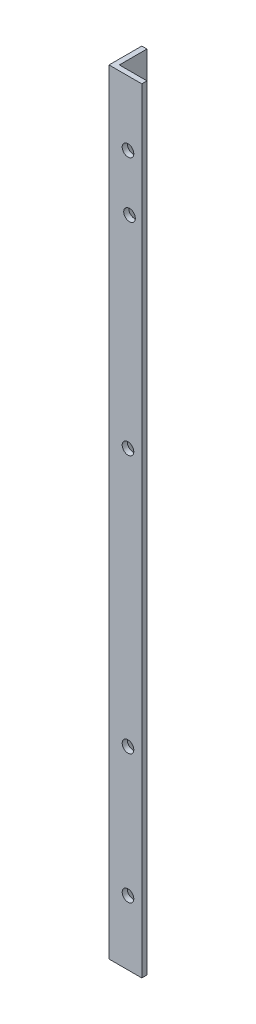
SolidWorks part; units mm, degrees
material "Alumina"
ref_plane "Front Plane" through (0, 0, 0) normal (0, 0, 1) x (1, 0, 0)
ref_plane "Top Plane" through (0, 0, 0) normal (0, 1, 0) x (1, 0, 0)
ref_plane "Right Plane" through (0, 0, 0) normal (1, 0, 0) x (0, 0, -1)
sketch "Sketch1" plane through (0, 0, 0) normal (0, 1, 0) x (1, 0, 0)
  line L0 (-13.7141, 0) -> (20.1365, 0) construction
  line L7 (0, 0) -> (12.7, 0)
  line L8 (0, 0) -> (0, 12.7)
  line L9 (2, 2) -> (12.7, 2)
  line L10 (2, 2) -> (2, 12.7)
  line L11 (0, 12.7) -> (2, 12.7)
  line L12 (12.7, 0) -> (12.7, 2)
  dimension "D1" = 12.7
  dimension "D2" = 12.7
  dimension "D3" = 2
extrude "Boss-Extrude1" add sketch "Sketch1" along normal blind 300
sketch "Sketch3" plane through (0, 0, -2) normal (0, 0, -1) x (-1, 0, 0)
  line L0 (-7.35, 300) -> (-7.35, 0) construction
  line L1 (-12.7, 300) -> (-2, 300) construction
  circle A2 centre (-7.35, 275) radius 2.25
  circle A6 centre (-7.35, 175) radius 2.25
  circle A7 centre (-7.35, 75) radius 2.25
  dimension "D2" = 4.5
  dimension "D1" = 25
extrude "Cut-Extrude1" cut sketch "Sketch3" against normal blind 300
sketch "Sketch6" plane through (2, 0, 0) normal (1, 0, 0) x (0, 0, -1)
  line L0 (7.35, 300) -> (7.35, 0) construction
  line L1 (2, 300) -> (12.7, 300) construction
  line L2 (2, 0) -> (12.7, 0) construction
  circle A0 centre (7.35, 225) radius 2.25
  circle A2 centre (7.35, 125) radius 2.25
  circle A3 centre (7.35, 25) radius 2.25
  dimension "D2" = 4.5
  dimension "D1" = 75
extrude "Cut-Extrude2" cut sketch "Sketch6" against normal blind 10
sketch "Sketch7" plane through (0, 0, 0) normal (0, 0, 1) x (1, 0, 0)
  circle A0 centre (7.94, 253.6) radius 1.85
sketch "Sketch8" plane through (0, 0, 0) normal (0, 0, 1) x (1, 0, 0)
  circle A0 centre (7.94, 253.6) radius 2.25
  circle A1 centre (7.35, 25) radius 2.25
  dimension "D1" = 4.5
extrude "Cut-Extrude3" cut sketch "Sketch8" against normal blind 10
